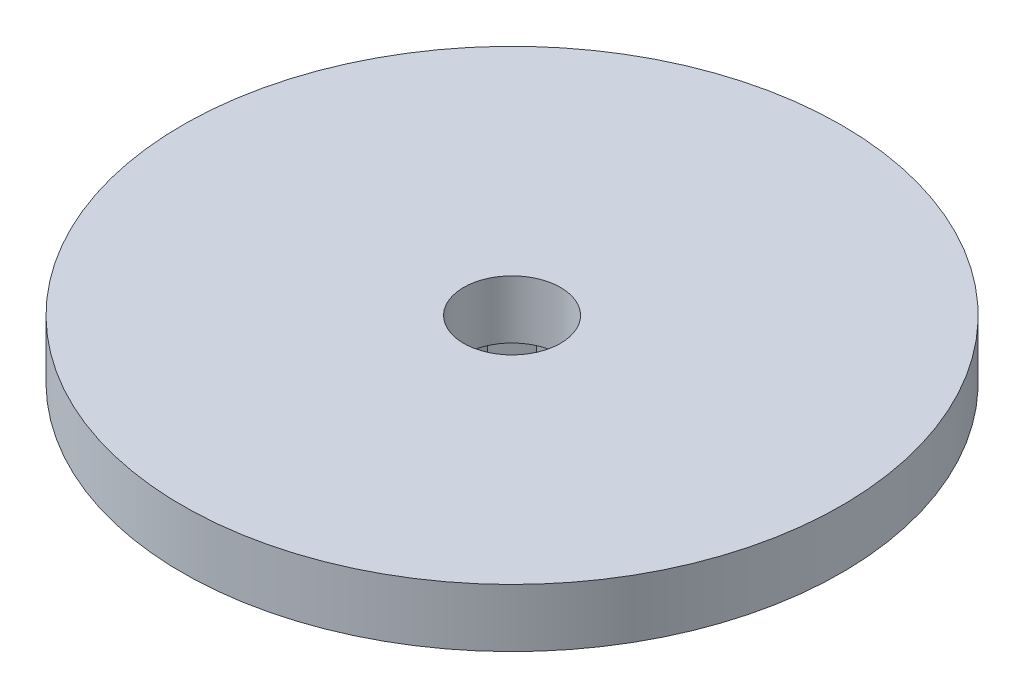
SolidWorks part; units mm, degrees
ref_plane "Plan de face" through (0, 0, 0) normal (0, 0, 1) x (1, 0, 0)
ref_plane "Plan de dessus" through (0, 0, 0) normal (0, 1, 0) x (1, 0, 0)
ref_plane "Plan de droite" through (0, 0, 0) normal (1, 0, 0) x (0, 0, -1)
sketch "Esquisse1" plane through (0, 0, 0) normal (0, 0, 1) x (1, 0, 0)
  line L0 (0, 0) -> (0, 20.6845) construction
  line L1 (-8.5, 3.7) -> (-1.25, 3.7)
  line L2 (-8.5, 3.7) -> (-8.5, 2.2)
  line L3 (-8.5, 2.2) -> (-3.9, 2.2)
  line L4 (-1.25, 3.7) -> (-1.25, 2.2)
  line L6 (-3.9, 2.2) -> (-3.9, 0)
  line L7 (-3.9, 0) -> (-2.2, 0)
  line L8 (-2.2, 2.2) -> (-2.2, 0)
  line L9 (-2.2, 2.2) -> (-1.25, 2.2)
  dimension "D1" = 1.7
  dimension "D2" = 1.5
  dimension "D3" = 1.25
  dimension "D4" = 3.9
  dimension "D5" = 8.5
  dimension "D6" = 2.2
revolve "Révolution1" add sketch "Esquisse1" angle 360 about L0
sketch "Esquisse2" plane through (0, 0, 0) normal (0, -1, 0) x (1, 0, 0)
  line L1 (1.2745, -1.9075) -> (1.9075, -1.2745)
  line L2 (1.9075, -1.2745) -> (2.25, -0.4476)
  line L3 (2.25, -0.4476) -> (2.25, 0.4476)
  line L4 (2.25, 0.4476) -> (1.9075, 1.2745)
  line L5 (1.9075, 1.2745) -> (1.2745, 1.9075)
  line L6 (1.2745, 1.9075) -> (0.4476, 2.25)
  line L7 (0.4476, 2.25) -> (-0.4476, 2.25)
  line L8 (-0.4476, 2.25) -> (-1.2745, 1.9075)
  line L9 (-1.2745, 1.9075) -> (-1.9075, 1.2745)
  line L10 (-1.9075, 1.2745) -> (-2.25, 0.4476)
  line L11 (-2.25, 0.4476) -> (-2.25, -0.4476)
  line L12 (-2.25, -0.4476) -> (-1.9075, -1.2745)
  line L13 (-1.9075, -1.2745) -> (-1.2745, -1.9075)
  line L14 (-1.2745, -1.9075) -> (-0.4476, -2.25)
  line L15 (-0.4476, -2.25) -> (0.4476, -2.25)
  line L16 (0.4476, -2.25) -> (1.2745, -1.9075)
  circle A0 centre (0, 0) radius 2.25 construction
  circle A1 centre (0, 0) radius 2.2 construction
  dimension "D1" = 4.5
extrude "Enlèv. mat.-Extru.1" cut sketch "Esquisse2" against normal blind 2.2
